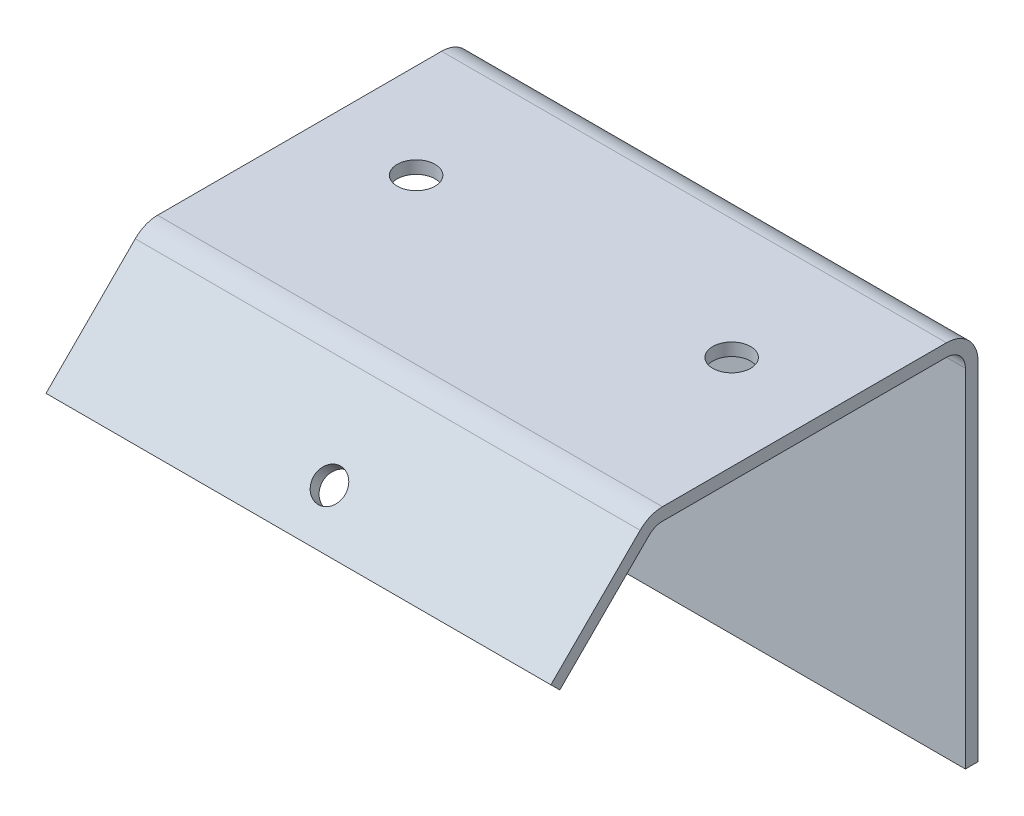
SolidWorks part; units mm, degrees
ref_plane "前视基准面" through (0, 0, 0) normal (0, 0, 1) x (1, 0, 0)
ref_plane "上视基准面" through (0, 0, 0) normal (0, 1, 0) x (1, 0, 0)
ref_plane "右视基准面" through (0, 0, 0) normal (1, 0, 0) x (0, 0, -1)
ref_plane "基准面1" through (-40, 0, 0) normal (1, 0, 0) x (0, 0, -1)
sketch "草图8" plane through (0, 0, 0) normal (0, 0, 1) x (1, 0, 0)
  circle A0 centre (0, 25) radius 4
sketch3d "3D草图1"
  line L0 (-25, 53.8, 24.031) -> (-25, 63.8, 24.031)
sketch3d "3D草图2"
  line L0 (25, 53.8, 24.031) -> (25, 63.8, 24.031)
sketch3d "3D草图3"
  line L0 (0, 51.9975, 58.3765) -> (0, 44.9265, 65.4475)
sketch "草图12" plane through (-40, 0, 0) normal (1, 0, 0) x (0, 0, -1)
  line L0 (0, 0) -> (0, 55)
  line L1 (-5, 60) -> (-50, 60)
  line L2 (-53.5355, 58.5355) -> (-67.6777, 44.3934)
  line L3 (-67.6777, 44.3934) -> (-66.2634, 42.9792)
  line L4 (-66.2634, 42.9792) -> (-52.1213, 57.1213)
  line L5 (-50, 58) -> (-5, 58)
  line L6 (-2, 55) -> (-2, 0)
  line L7 (-2, 0) -> (0, 0)
  arc A0 (0, 55) -> (-5, 60) centre (-5.0001, 54.9999) ccw
  arc A1 (-50, 60) -> (-53.5355, 58.5355) centre (-50, 55.0003) ccw
  arc A2 (-52.1213, 57.1213) -> (-50, 58) centre (-50, 55) cw
  arc A3 (-5, 58) -> (-2, 55) centre (-5.0001, 54.9999) cw
extrude "凸台-拉伸3" add sketch "草图12" along normal blind 80
sketch "草图13" plane through (0, 0, 0) normal (0, 0, 1) x (1, 0, 0)
  circle A0 centre (0, 25) radius 4
extrude "切除-拉伸2" cut sketch "草图13" along normal through all
sketch3d "3D草图4"
  line L0 (-25, 53.8, 24.031) -> (-25, 63.8, 24.031)
sweep "切除-扫描8" cut path "3D草图4" circular profile diameter 6 parameters "D3"=6
sketch3d "3D草图5"
  line L0 (25, 53.8, 24.031) -> (25, 63.8, 24.031)
sweep "切除-扫描10" cut path "3D草图5" circular profile diameter 6 parameters "D3"=6
sketch3d "3D草图6"
  line L0 (0, 44.9265, 58.3765) -> (0, 51.9975, 65.4475)
sweep "切除-扫描12" cut path "3D草图6" circular profile diameter 5 parameters "D3"=5
sketch "折弯-线1" [suppressed] plane through (0, 0, 0) normal (0, 1, 0) x (1, 0, 0)
sketch "边界框1" [suppressed] plane through (0, 0, 0) normal (0, 1, 0) x (1, 0, 0)
